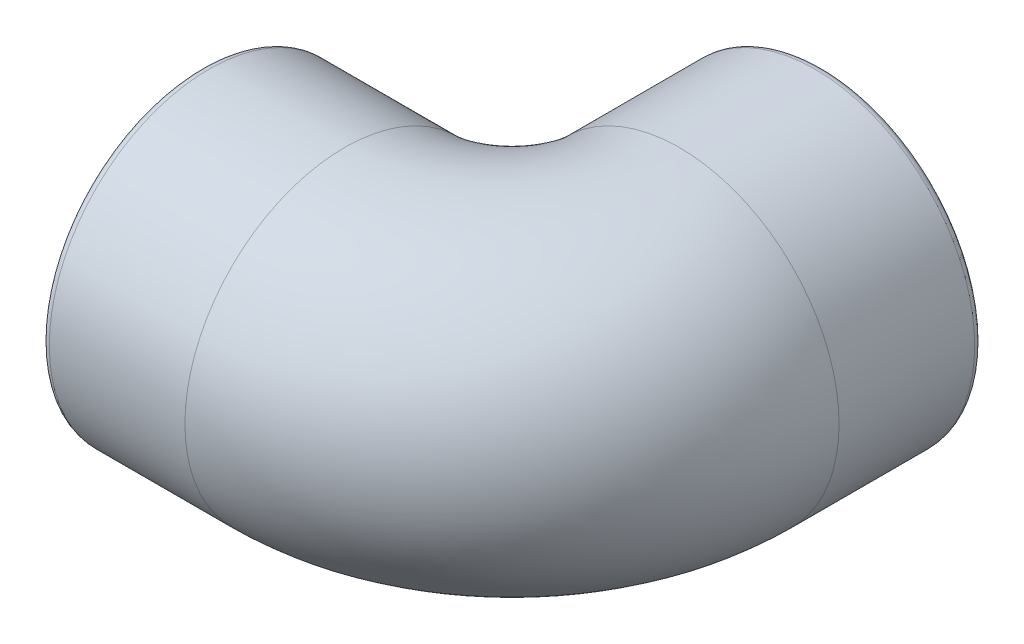
SolidWorks part; units mm, degrees
ref_plane "Alzado" through (0, 0, 0) normal (0, 0, 1) x (1, 0, 0)
ref_plane "Planta" through (0, 0, 0) normal (0, 1, 0) x (1, 0, 0)
ref_plane "Vista lateral" through (0, 0, 0) normal (1, 0, 0) x (0, 0, -1)
sketch "Croquis1" plane through (0, 0, 0) normal (1, 0, 0) x (0, 0, -1)
  line L0 (0, 0) -> (-21, 0) construction
  line L1 (0, 0) -> (0, 24.2227) construction
  circle A0 centre (-21, 0) radius 20
  dimension "D1" = 40
  dimension "D2" = 21
revolve "Revolución-Lámina1" add sketch "Croquis1" angle 90 about L1 wall 3
sketch "Croquis3" plane through (0, 0, 0) normal (-1, 0, 0) x (0, 0, 1)
  circle A0 centre (21, 0) radius 17 construction
  circle A1 centre (21, 0) radius 20
  circle A2 centre (21, 0) radius 20
  circle A3 centre (21, 0) radius 17
  dimension "D1" = 0
extrude "Extruir1" add sketch "Croquis3" along normal blind 18
sketch "Croquis4" plane through (0, 0, 0) normal (0, 0, -1) x (-1, 0, 0)
  circle A0 centre (-21, 0) radius 20 construction
  circle A1 centre (-21, 0) radius 20
  circle A2 centre (-21, 0) radius 17 construction
  circle A3 centre (-21, 0) radius 17
extrude "Extruir2" add sketch "Croquis4" along normal blind 18
fillet "Redondeo1" radius 1 2 edges at (1, 0, -18) (-18, 0, 41)
